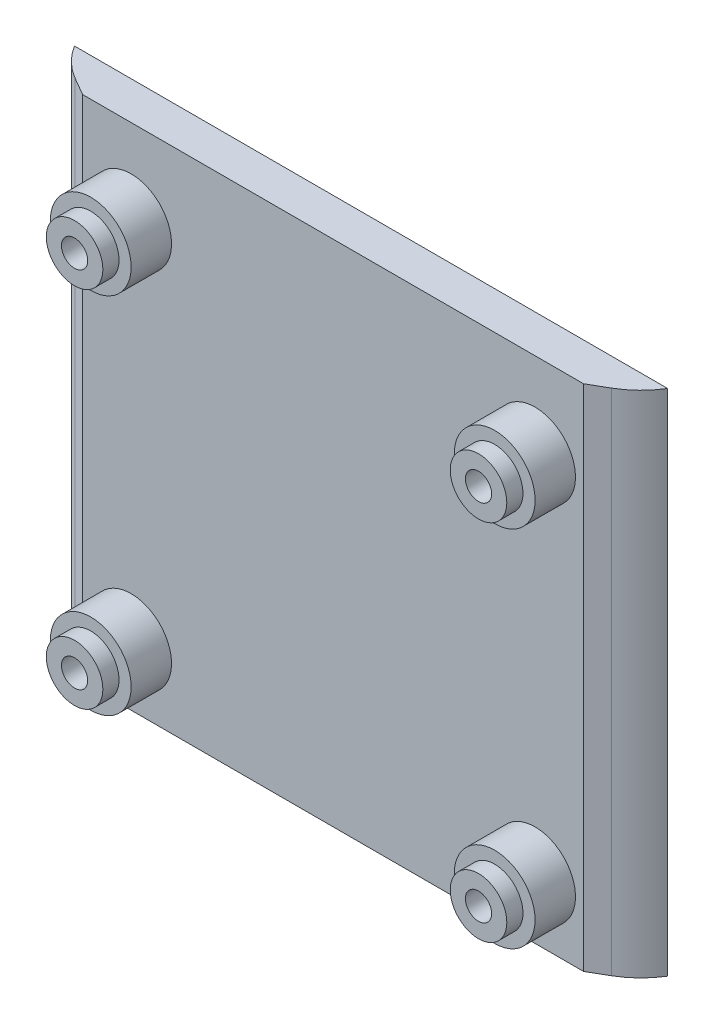
SolidWorks part; units mm, degrees
ref_plane "Plan de face" through (0, 0, 0) normal (0, 0, 1) x (1, 0, 0)
ref_plane "Plan de dessus" through (0, 0, 0) normal (0, 1, 0) x (1, 0, 0)
ref_plane "Plan de droite" through (0, 0, 0) normal (1, 0, 0) x (0, 0, -1)
sketch "Esquisse1" plane through (0, 0, 0) normal (0, 0, 1) x (1, 0, 0)
  line L1 (0, 0) -> (62, 0)
  line L2 (0, 0) -> (0, 60)
  line L3 (0, 60) -> (62, 60)
  line L4 (62, 0) -> (62, 60)
  dimension "D1" = 62
  dimension "D2" = 60
extrude "Boss.-Extru.1" add sketch "Esquisse1" along normal blind 10
sketch "Esquisse3" plane through (0, 0, 10) normal (0, 0, 1) x (1, 0, 0)
  line L0 (0, 60) -> (62, 0) construction
  line L1 (62, 0) -> (0, 0) construction
  line L2 (0, 0) -> (62, 60) construction
  line L3 (62, 0) -> (62, 60) construction
  line L4 (62, 60) -> (0, 60) construction
  line L6 (0, 60) -> (0, 0) construction
  circle A0 centre (6, 52.5) radius 5
  circle A1 centre (56, 7.5) radius 5
  circle A2 centre (6, 7.5) radius 5
  circle A3 centre (56, 52.5) radius 5
  dimension "D1" = 10
  dimension "D4" = 10
  dimension "D8" = 10
  dimension "D9" = 10
  dimension "D2" = 7.5
  dimension "D3" = 7.5
  dimension "D5" = 6
  dimension "D6" = 50
  dimension "D7" = 50
  dimension "D10" = 6
  dimension "D11" = 7.5
  dimension "D12" = 7.5
extrude "Boss.-Extru.2" add sketch "Esquisse3" along normal blind 5
sketch "Esquisse4" plane through (0, 0, 15) normal (0, 0, 1) x (1, 0, 0)
  circle A0 centre (6, 52.5) radius 3.5
  circle A1 centre (56, 52.5) radius 3.5
  circle A2 centre (56, 7.5) radius 3.5
  circle A3 centre (6, 7.5) radius 3.5
  dimension "D1" = 7
  dimension "D2" = 7
  dimension "D3" = 7
  dimension "D4" = 7
extrude "Boss.-Extru.3" add sketch "Esquisse4" along normal blind 2
sketch "Esquisse5" plane through (0, 0, 17) normal (0, 0, 1) x (1, 0, 0)
  circle A0 centre (6, 52.5) radius 1.625
  circle A1 centre (56, 52.5) radius 1.625
  circle A2 centre (56, 7.5) radius 1.625
  circle A3 centre (6, 7.5) radius 1.625
  dimension "D1" = 3.25
  dimension "D2" = 3.25
  dimension "D3" = 3.25
  dimension "D4" = 3.25
extrude "Enlèv. mat.-Extru.2" cut sketch "Esquisse5" against normal through all
sketch "Esquisse7" plane through (0, 60, 0) normal (0, 1, 0) x (1, 0, 0)
  line L1 (0, 0) -> (0, -10)
  line L2 (0, -10) -> (62, -10)
  line L4 (6, 51) -> (56, 51)
  line L6 (62, -10) -> (62, 0)
  line L17 (62, -10) -> (62, 0) construction
  arc A4 (62, 0) -> (56, 51) centre (-67.5663, 10.6098) ccw
  arc A5 (0, 0) -> (6, 51) centre (129.5663, 10.6098) cw
  point P20 (62, -5)
  dimension "D4" = 6
  dimension "D3" = 130
  dimension "D9" = 130
  dimension "D2" = 6
  dimension "D1" = 61
extrude "Boss.-Extru.4" add sketch "Esquisse7" along normal mid plane 6
sketch "Esquisse9" plane through (0, 63, 0) normal (0, 1, 0) x (1, 0, 0)
  line L0 (0, -10) -> (62, -10) construction
  line L1 (0, 0) -> (0, -10) construction
  line L2 (62, -10) -> (62, 0) construction
  circle A0 centre (31, 30) radius 11
  circle A1 centre (46.5, 14.5) radius 1.625
  circle A2 centre (15.5, 14.5) radius 1.625
  circle A3 centre (15.5, 45.5) radius 1.625
  circle A4 centre (15.5, 45.5) radius 1.625
  circle A5 centre (46.5, 45.5) radius 1.625
  circle A6 centre (56, 18) radius 1.5
  circle A7 centre (6, 18) radius 1.5
  point P21 (62, -5)
  dimension "D3" = 3.25
  dimension "D4" = 3.25
  dimension "D5" = 3.25
  dimension "D6" = 3.25
  dimension "D11" = 31
  dimension "D9" = 3.25
  dimension "D14" = 22
  dimension "D15" = 50
  dimension "D16" = 3
  dimension "D17" = 3
  dimension "D1" = 40
  dimension "D2" = 31
  dimension "D7" = 31
  dimension "D8" = 31
  dimension "D10" = 31
  dimension "D12" = 15.5
  dimension "D13" = 15.5
  dimension "D18" = 6
  dimension "D19" = 12
extrude "Enlèv. mat.-Extru.4" cut sketch "Esquisse9" against normal blind 10 contours A0 | A7 | A2 | A1 | A6 | A5 | A3
ref_plane "Plan1" through (0, 0, 0) normal (-0.9932, 0, -0.1168) x (-0.1168, 0, 0.9932)
sketch "Esquisse14" plane through (0, 63, 0) normal (0, 1, 0) x (1, 0, 0)
  line L0 (0, 0) -> (0, -10)
  line L1 (0, -10) -> (-6.9282, -6)
  line L3 (56, 51) -> (6, 51) construction
  line L4 (11.0445, 51) -> (6, 51)
  arc A0 (11.0445, 51) -> (0, 0) centre (129.9919, -1.4549) ccw
  arc A2 (6, 51) -> (-6.9282, -6) centre (92.8016, 1.3464) ccw
  dimension "D1" = 100
  dimension "D2" = 8
  dimension "D3" = 60
extrude "Boss.-Extru.6" add sketch "Esquisse14" against normal blind 63
ref_plane "Plan2" through (31, 0, 0) normal (1, 0, 0) x (0, 0, -1)
mirror "Symétrie1" about plane through (31, 0, 0) normal (1, 0, 0) of "Boss.-Extru.6"
sketch "Esquisse16" plane through (0, 57, 0) normal (0, -1, 0) x (1, 0, 0)
  line L1 (10.0415, -18) -> (8.0207, -14.5)
  line L2 (8.0207, -14.5) -> (3.9793, -14.5)
  line L3 (3.9793, -14.5) -> (1.9585, -18)
  line L4 (1.9585, -18) -> (3.9793, -21.5)
  line L5 (3.9793, -21.5) -> (8.0207, -21.5)
  line L6 (8.0207, -21.5) -> (10.0415, -18)
  line L7 (60.0415, -18) -> (58.0207, -14.5)
  line L8 (58.0207, -14.5) -> (53.9793, -14.5)
  line L9 (53.9793, -14.5) -> (51.9585, -18)
  line L10 (51.9585, -18) -> (53.9793, -21.5)
  line L11 (53.9793, -21.5) -> (58.0207, -21.5)
  line L12 (58.0207, -21.5) -> (60.0415, -18)
  circle A0 centre (6, -18) radius 3.5 construction
  circle A1 centre (56, -18) radius 3.5 construction
  dimension "D1" = 7
  dimension "D2" = 7
extrude "Enlèv. mat.-Extru.6" cut sketch "Esquisse16" against normal blind 4
sketch "Esquisse18" plane through (0, 0, 0) normal (1, 0, 0) x (0, 0, -1)
  line L1 (-6, 0) -> (51, 0) construction
  line L2 (51, 63) -> (51, 0) construction
  line L3 (51, 63) -> (-6, 63) construction
  line L4 (51, 53) -> (51, 0)
  line L5 (51, 0) -> (0, 0)
  arc A0 (51, 53) -> (0, 0) centre (68.4179, -14.7984) ccw
  dimension "D3" = 70
  dimension "D1" = 10
  dimension "D2" = 10
extrude "Enlèv. mat.-Extru.7" cut sketch "Esquisse18" along normal mid plane 204
sketch "Esquisse19" plane through (0, 57, 0) normal (0, -1, 0) x (1, 0, 0)
  line L1 (10, -51) -> (52, -51)
  line L2 (10, -51) -> (10, -9)
  line L3 (10, -9) -> (52, -9)
  line L4 (52, -51) -> (52, -9)
  line L5 (10, -51) -> (52, -9) construction
  line L6 (10, -9) -> (52, -51) construction
  point P0 (31, -30)
  dimension "D1" = 42
  dimension "D2" = 42
extrude "Enlèv. mat.-Extru.8" cut sketch "Esquisse19" against normal blind 1 and the other way blind 23
chamfer "Chanfrein1" distance 1 angle 45 1 edges at (31, 63, -19)
fillet "Congé1" radius 10 2 edges at (-6.9282, 31.5, 6) (68.9282, 31.5, 6)
sketch "Esquisse20" plane through (0, 63, 0) normal (0, 1, 0) x (1, 0, 0)
  line L1 (82.2171, -5.3028) -> (-14.5753, -5.3028)
  line L2 (82.2171, -5.3028) -> (82.2171, 72.9774)
  line L3 (82.2171, 72.9774) -> (-14.5753, 72.9774)
  line L4 (-14.5753, -5.3028) -> (-14.5753, 72.9774)
extrude "Enlèv. mat.-Extru.10" cut sketch "Esquisse20" against normal through all
